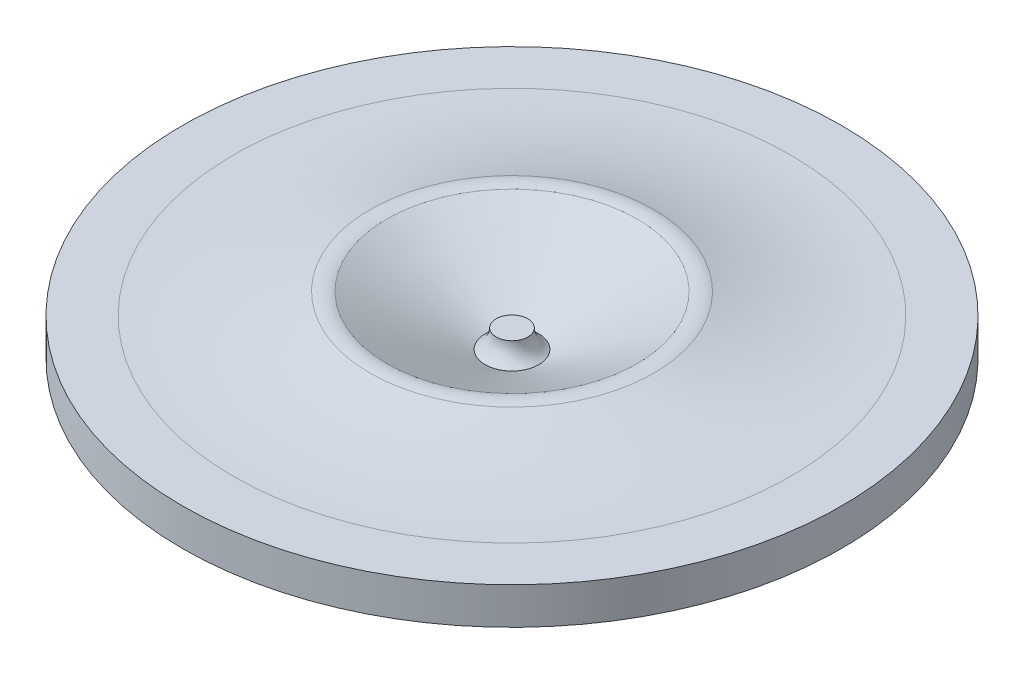
SolidWorks part; units mm, degrees
ref_plane "Front Plane" through (0, 0, 0) normal (0, 0, 1) x (1, 0, 0)
ref_plane "Top Plane" through (0, 0, 0) normal (0, 1, 0) x (1, 0, 0)
ref_plane "Right Plane" through (0, 0, 0) normal (1, 0, 0) x (0, 0, -1)
sketch "Sketch1" plane through (0, 0, 1.3838) normal (0, 0, 1) x (0, -1, 0)
  line L0 (-6.4826, -22.2367) -> (-16.4826, -22.2367)
  line L1 (-6.4826, -22.2367) -> (-6.4826, 102.7633)
  line L2 (-6.4826, 102.7633) -> (-20.4826, 102.7633)
  line L3 (-20.4826, -147.2367) -> (-20.4826, -127.8617)
  line L4 (-20.4826, 83.3883) -> (-20.4826, 102.7633)
  line L5 (-20.4826, 83.3883) -> (-20.4826, 102.7633)
  line L6 (-20.4826, -147.2367) -> (-20.4826, -127.8617)
  line L7 (-16.4826, -22.2367) -> (-16.4826, -16.2367)
  line L8 (-9.4661, -12.0796) -> (-28.4826, 25.2633)
  arc A0 (-20.4826, -127.8617) -> (-28.4826, -76.0273) centre (-192.4084, -127.8617) ccw
  arc A1 (-28.4826, 31.5538) -> (-20.4826, 83.3883) centre (-192.4084, 83.3883) ccw
  arc A2 (-28.4826, 31.5538) -> (-20.4826, 83.3883) centre (-192.4084, 83.3883) ccw
  arc A3 (-20.4826, -127.8617) -> (-28.4826, -76.0273) centre (-192.4084, -127.8617) ccw
  arc A4 (-28.4826, -69.7367) -> (-28.4826, -76.0273) centre (-18.5358, -72.882) ccw
  arc A5 (-28.4826, 31.5538) -> (-28.4826, 25.2633) centre (-18.5358, 28.4085) ccw
  arc A6 (-28.4826, 31.5538) -> (-28.4826, 25.2633) centre (-18.5358, 28.4085) ccw
  arc A7 (-28.4826, -69.7367) -> (-28.4826, -76.0273) centre (-18.5358, -72.882) ccw
  arc A8 (-16.4826, -16.2367) -> (-8.4826, -8.2367) centre (-16.4826, -8.2367) ccw construction
  arc A9 (-16.4826, -16.2367) -> (-9.4661, -12.0796) centre (-16.4826, -8.2367) ccw
  spline S0 degree 3 poles (-28.4807, 24.8448) (-27.7763, 23.4821) (-26.6185, 21.2421) (-25.2097, 18.514) (-23.8084, 15.7995) (-22.1586, 12.6015) (-20.3023, 9.0001) (-18.45, 5.4039) (-16.618, 1.8444) (-15.0844, -1.1378) (-13.9431, -3.3586) (-12.7963, -5.5906) (-11.1314, -8.8331) (-9.5648, -11.8868) (-8.6847, -13.6032) (-8.4826, -13.9974) knots 0 0 0 0 0.105346 0.173178 0.210852 0.315151 0.420355 0.489085 0.592954 0.69527 0.719342 0.764394 0.867575 0.96959 1 1 1 1 construction
  point P26 (-16.4826, -8.2367)
revolve "Revolve1" add sketch "Sketch1" angle 360 about L0
